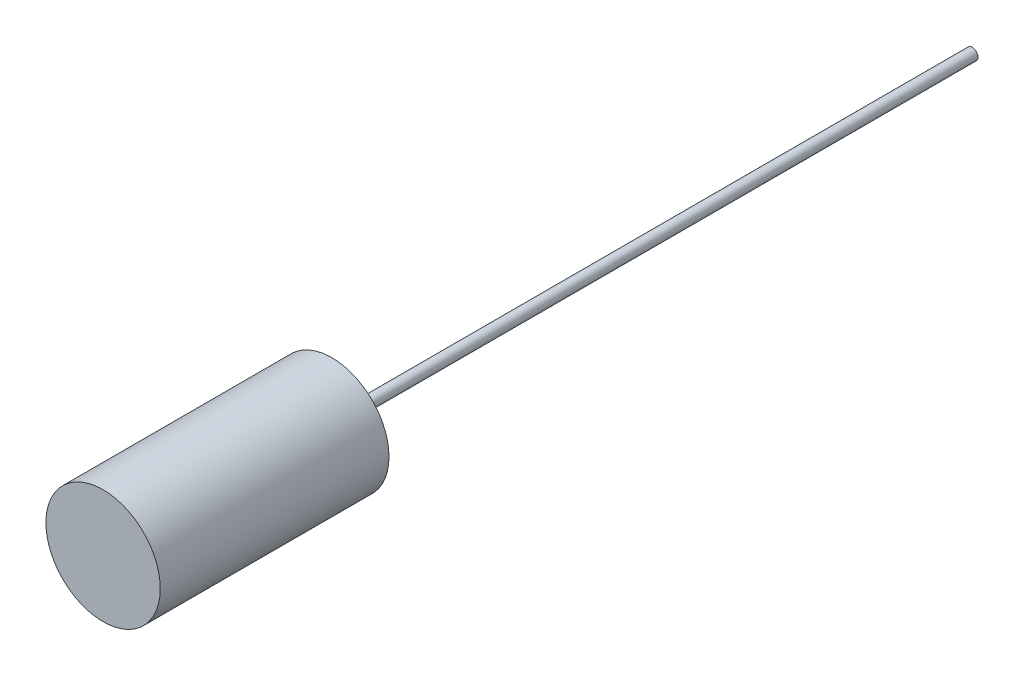
SolidWorks part; units mm, degrees
ref_plane "前视基准面" through (0, 0, 0) normal (0, 0, 1) x (1, 0, 0)
ref_plane "上视基准面" through (0, 0, 0) normal (0, 1, 0) x (1, 0, 0)
ref_plane "右视基准面" through (0, 0, 0) normal (1, 0, 0) x (0, 0, -1)
sketch "草图1" plane through (0, 0, 0) normal (0, 0, 1) x (1, 0, 0)
  circle A0 centre (0, 0) radius 5
extrude "凸台-拉伸1" add sketch "草图1" along normal blind 20
sketch "草图2" plane through (0, 0, 0) normal (0, 0, -1) x (-1, 0, 0)
  circle A0 centre (0, 0) radius 0.5
extrude "凸台-拉伸2" add sketch "草图2" along normal blind 56
